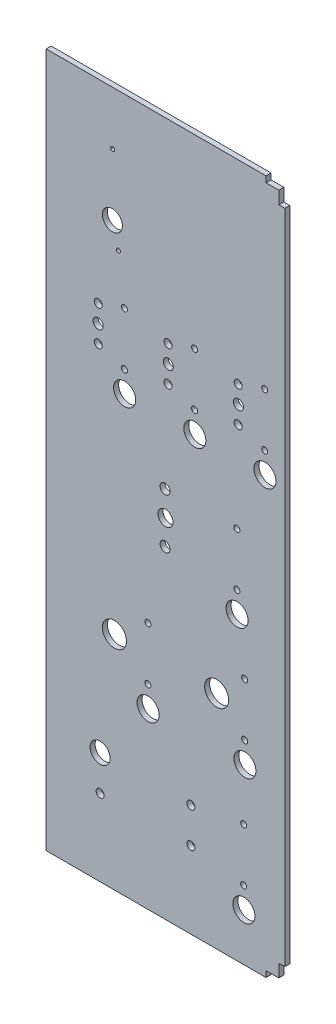
SolidWorks part; units mm, degrees
material "PE High Density"
ref_plane "Front Plane" through (0, 0, 0) normal (0, 0, 1) x (1, 0, 0)
ref_plane "Top Plane" through (0, 0, 0) normal (0, 1, 0) x (1, 0, 0)
ref_plane "Right Plane" through (0, 0, 0) normal (1, 0, 0) x (0, 0, -1)
sketch "Sketch1" plane through (0, 0, 0) normal (0, 0, 1) x (1, 0, 0)
  line L1 (0, 0) -> (302.3362, 0)
  line L2 (0, 0) -> (0, 879.8306)
  line L3 (0, 879.8306) -> (302.3362, 879.8306)
  line L4 (302.3362, 0) -> (302.3362, 879.8306)
  dimension "D1" = 302.3362
  dimension "D2" = 879.8306
extrude "Boss-Extrude1" add sketch "Sketch1" along normal blind 6.35
sketch "Sketch2" plane through (0, 0, 6.35) normal (0, 0, 1) x (1, 0, 0)
  line L2 (0, 879.8306) -> (0, 0) construction
  line L3 (0, 0) -> (302.3362, 0) construction
  circle A0 centre (68.3387, 97.1296) radius 5.08
  circle A1 centre (68.3387, 141.6304) radius 12.7
  circle A2 centre (183.2737, 97.1296) radius 5.08
  circle A3 centre (183.2737, 141.6304) radius 5.08
  dimension "D1" = 10.16
  dimension "D6" = 25.4
  dimension "D2" = 44.5008
  dimension "D3" = 114.935
  dimension "D4" = 68.3387
  dimension "D5" = 97.1296
extrude "Cut-Extrude1" cut sketch "Sketch2" against normal through all
sketch "Sketch3" plane through (0, 0, 6.35) normal (0, 0, 1) x (1, 0, 0)
  line L0 (250.2662, 87.122) -> (250.2662, 154.178) construction
  line L1 (128.8542, 247.142) -> (128.8542, 314.198) construction
  line L2 (251.5362, 247.142) -> (251.5362, 314.198) construction
  line L3 (241.6302, 407.1366) -> (241.6302, 474.1926) construction
  line L4 (276.9362, 577.8246) -> (276.9362, 644.8806) construction
  line L5 (188.0362, 577.8246) -> (188.0362, 644.8806) construction
  line L6 (99.1362, 577.8246) -> (99.1362, 644.8806) construction
  line L7 (302.3362, 0) -> (302.3362, 879.8306) construction
  line L8 (0, 0) -> (302.3362, 0) construction
  circle A0 centre (250.2662, 87.122) radius 3.81
  circle A1 centre (250.2662, 154.178) radius 3.81
  circle A2 centre (251.5362, 247.142) radius 3.81
  circle A3 centre (251.5362, 314.198) radius 3.81
  circle A4 centre (128.8542, 247.142) radius 3.81
  circle A5 centre (128.8542, 314.198) radius 3.81
  circle A6 centre (241.6302, 407.1366) radius 3.81
  circle A7 centre (241.6302, 474.1926) radius 3.81
  circle A8 centre (276.9362, 577.8246) radius 3.81
  circle A9 centre (276.9362, 644.8806) radius 3.81
  circle A10 centre (188.0362, 577.8246) radius 3.81
  circle A11 centre (188.0362, 644.8806) radius 3.81
  circle A12 centre (99.1362, 577.8246) radius 3.81
  circle A13 centre (99.1362, 644.8806) radius 3.81
  dimension "D1" = 7.62
  dimension "D2" = 67.056
  dimension "D3" = 52.07
  dimension "D4" = 87.122
  dimension "D5" = 122.682
  dimension "D6" = 92.964
  dimension "D7" = 50.8
  dimension "D8" = 92.9386
  dimension "D9" = 60.706
  dimension "D10" = 103.632
  dimension "D11" = 25.4
  dimension "D12" = 88.9
  dimension "D13" = 88.9
extrude "Cut-Extrude2" cut sketch "Sketch3" against normal through all
sketch "Sketch4" plane through (0, 0, 6.35) normal (0, 0, 1) x (1, 0, 0)
  line L0 (0, 879.8306) -> (0, 0) construction
  line L1 (0, 0) -> (302.3362, 0) construction
  circle A0 centre (86.4362, 280.67) radius 15.24
  circle A1 centre (215.9762, 280.67) radius 15.24
  dimension "D4" = 30.48
  dimension "D1" = 129.54
  dimension "D2" = 86.4362
  dimension "D3" = 280.67
extrude "Cut-Extrude3" cut sketch "Sketch4" against normal through all
sketch "Sketch5" plane through (0, 0, 6.35) normal (0, 0, 1) x (1, 0, 0)
  line L0 (302.3362, 0) -> (302.3362, 879.8306) construction
  line L1 (0, 0) -> (302.3362, 0) construction
  circle A0 centre (250.5202, 60.2451) radius 13.97
  circle A1 centre (251.7902, 220.2651) radius 13.97
  circle A2 centre (129.1082, 220.2651) radius 13.97
  circle A3 centre (241.8842, 380.2597) radius 13.97
  circle A4 centre (277.1902, 550.9477) radius 13.97
  circle A5 centre (188.2902, 550.9477) radius 13.97
  circle A6 centre (99.3902, 550.9477) radius 13.97
  dimension "D10" = 27.94
  dimension "D1" = 88.9
  dimension "D2" = 88.9
  dimension "D3" = 170.688
  dimension "D4" = 35.306
  dimension "D5" = 122.682
  dimension "D6" = 159.9946
  dimension "D7" = 9.906
  dimension "D8" = 160.02
  dimension "D9" = 1.27
  dimension "D11" = 51.816
  dimension "D12" = 60.2451
extrude "Cut-Extrude4" cut sketch "Sketch5" against normal through all
sketch "Sketch6" plane through (0, 0, 6.35) normal (0, 0, 1) x (1, 0, 0)
  line L0 (302.3362, 0) -> (302.3362, 879.8306) construction
  line L1 (302.3362, 879.8306) -> (0, 879.8306) construction
  circle A0 centre (151.1427, 440.6646) radius 9.525
  circle A1 centre (243.5987, 611.3526) radius 6.35
  circle A2 centre (154.6987, 611.3526) radius 6.35
  circle A3 centre (65.7987, 611.3526) radius 6.35
  dimension "D7" = 12.7
  dimension "D8" = 19.05
  dimension "D1" = 170.688
  dimension "D2" = 85.344
  dimension "D3" = 88.9
  dimension "D4" = 88.9
  dimension "D5" = 58.7375
  dimension "D6" = 268.478
extrude "Cut-Extrude5" cut sketch "Sketch6" against normal through all
sketch "Sketch7" plane through (0, 0, 6.35) normal (0, 0, 1) x (1, 0, 0)
  line L0 (302.3362, 0) -> (302.3362, 879.8306) construction
  line L1 (302.3362, 879.8306) -> (0, 879.8306) construction
  circle A0 centre (150.6466, 408.9185) radius 6.35
  circle A1 centre (150.6466, 472.4107) radius 6.35
  circle A2 centre (65.9614, 589.1375) radius 5.08
  circle A3 centre (65.9614, 633.5677) radius 5.08
  circle A4 centre (154.36, 589.1375) radius 5.08
  circle A5 centre (154.36, 633.5677) radius 5.08
  circle A6 centre (243.26, 589.1375) radius 5.08
  circle A7 centre (243.26, 633.5677) radius 5.08
  dimension "D9" = 12.7
  dimension "D10" = 10.16
  dimension "D1" = 63.4922
  dimension "D2" = 44.4302
  dimension "D3" = 88.3986
  dimension "D4" = 88.9
  dimension "D5" = 116.7268
  dimension "D6" = 59.0762
  dimension "D7" = 84.6852
  dimension "D8" = 246.2629
extrude "Cut-Extrude6" cut sketch "Sketch7" against normal through all
sketch "Sketch8" plane through (0, 0, 6.35) normal (0, 0, 1) x (1, 0, 0)
  line L0 (0, 879.8306) -> (0, 0) construction
  line L1 (302.3362, 879.8306) -> (0, 879.8306) construction
  circle A0 centre (84.2645, 811.9745) radius 2.54
  circle A1 centre (91.5733, 704.2595) radius 2.54
  dimension "D1" = 5.08
  dimension "D2" = 7.3088
  dimension "D3" = 107.7151
  dimension "D4" = 84.2645
  dimension "D5" = 67.8561
extrude "Cut-Extrude7" cut sketch "Sketch8" against normal through all
sketch "Sketch9" plane through (0, 0, 6.35) normal (0, 0, 1) x (1, 0, 0)
  line L0 (0, 879.8306) -> (0, 0) construction
  line L1 (302.3362, 879.8306) -> (0, 879.8306) construction
  line L2 (278.5872, 0) -> (278.5872, 7.62)
  line L3 (0, 0) -> (302.3362, 0) construction
  line L4 (278.5872, 7.62) -> (294.7162, 7.62)
  line L5 (294.7162, 7.62) -> (294.7162, 23.749)
  line L6 (294.7162, 23.749) -> (302.3362, 23.749)
  line L7 (302.3362, 0) -> (302.3362, 879.8306) construction
  line L8 (278.5872, 0) -> (302.3362, 0)
  line L9 (302.3362, 0) -> (302.3362, 23.749)
  line L10 (0, 439.9153) -> (302.3362, 439.9153) construction
  line L11 (302.3362, 879.8306) -> (302.3362, 856.0816)
  line L12 (278.5872, 879.8306) -> (302.3362, 879.8306)
  line L13 (294.7162, 856.0816) -> (302.3362, 856.0816)
  line L14 (294.7162, 872.2106) -> (294.7162, 856.0816)
  line L15 (278.5872, 872.2106) -> (294.7162, 872.2106)
  line L16 (278.5872, 879.8306) -> (278.5872, 872.2106)
  circle A0 centre (83.82, 733.7806) radius 12.7
  dimension "D3" = 25.4
  dimension "D1" = 83.82
  dimension "D2" = 146.05
  dimension "D4" = 23.749
  dimension "D5" = 16.129
extrude "Cut-Extrude8" cut sketch "Sketch9" against normal through all
equation "\"D1@Sketch1\"=0.38+11.873-0.35"
equation "\"D2@Sketch1\"=34.862-(0.1115*2)"
